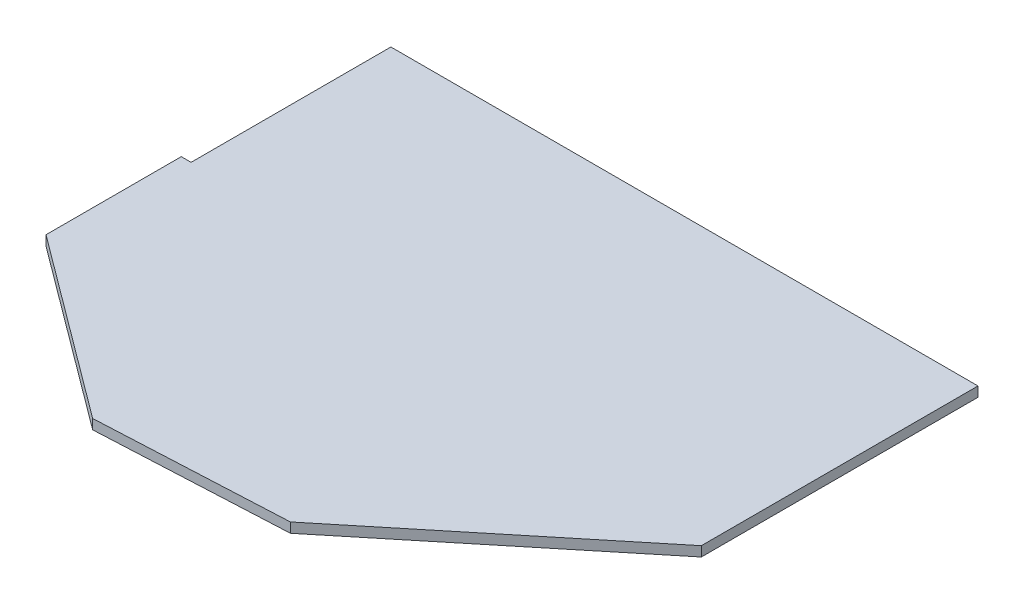
SolidWorks part; units mm, degrees
ref_plane "Front Plane" through (0, 0, 0) normal (0, 0, 1) x (1, 0, 0)
ref_plane "Top Plane" through (0, 0, 0) normal (0, 1, 0) x (1, 0, 0)
ref_plane "Right Plane" through (0, 0, 0) normal (1, 0, 0) x (0, 0, -1)
sketch "Sketch1" plane through (0, 0, 0) normal (0, 1, 0) x (1, 0, 0)
  line L0 (-71.1993, 0) -> (119.8007, 0)
  line L1 (119.8007, 0) -> (119.8007, -90)
  line L2 (119.8007, -90) -> (46.2729, -150.1553)
  line L3 (46.2729, -150.1553) -> (-15.0357, -153.1811)
  line L4 (-15.0357, -153.1811) -> (-74.3993, -109)
  line L5 (-74.3993, -109) -> (-74.3993, -65)
  line L6 (-74.3993, -65) -> (-71.1993, -65)
  line L7 (-71.1993, -65) -> (-71.1993, 0)
  point P6 (46.9827, -141.4423)
  point P10 (-15.9614, -145.1449)
  point P11 (40.0403, -150.2359)
  point P12 (-15.0357, -153.2422)
  dimension "D1" = 191
  dimension "D2" = 90
  dimension "D3" = 74
  dimension "D4" = 95
  dimension "D6" = 65
  dimension "D7" = 3.2
  dimension "D9" = 44
extrude "Boss-Extrude1" add sketch "Sketch1" along normal blind 3.2
sketch "Sketch3" plane through (0, 0, 0) normal (0, -1, 0) x (1, 0, 0)
  line L1 (-74.3993, 108.0683) -> (119.7657, 108.4369) construction
  line L2 (-74.3993, 65) -> (-74.3993, 109) construction
  line L3 (-5.3993, 152.7055) -> (-5.3993, 0) construction
  line L4 (-15.0357, 153.1811) -> (46.2729, 150.1553) construction
  line L5 (119.8007, 0) -> (-71.1993, 0) construction
  circle A0 centre (-5.3993, 108.1993) radius 12.3
  dimension "D3" = 24.6
  dimension "D1" = 45
  dimension "D2" = 69
extrude "Boss-Extrude2" add sketch "Sketch3" along normal blind 3.2
sketch "Sketch4" plane through (0, -3.2, 0) normal (0, -1, 0) x (1, 0, 0)
  circle A0 centre (-5.3993, 108.1993) radius 4
  dimension "D1" = 8
extrude "Boss-Extrude3" add sketch "Sketch4" along normal blind 4
